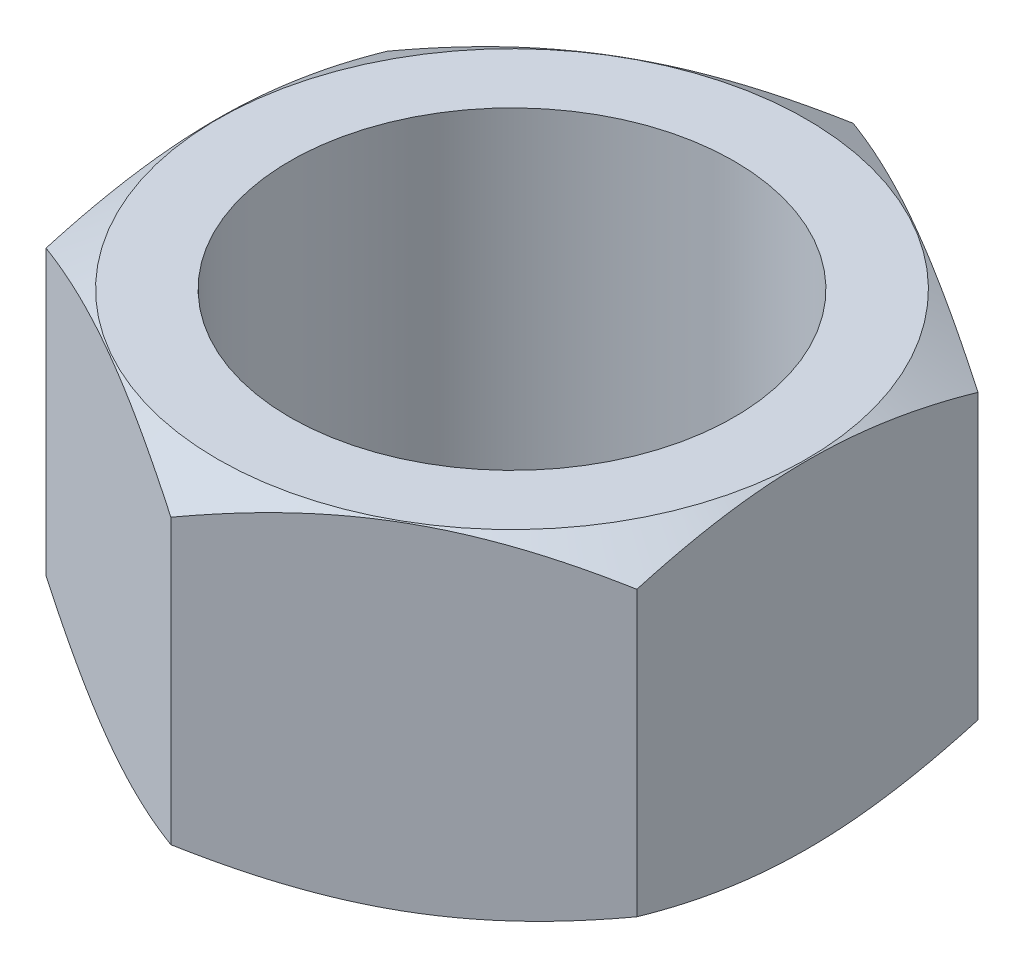
SolidWorks part; units mm, degrees
ref_plane "Front Plane" through (0, 0, 0) normal (0, 0, 1) x (1, 0, 0)
ref_plane "Top Plane" through (0, 0, 0) normal (0, 1, 0) x (1, 0, 0)
ref_plane "Right Plane" through (0, 0, 0) normal (1, 0, 0) x (0, 0, -1)
sketch "Sketch2" plane through (0, 0, 0) normal (0, 1, 0) x (1, 0, 0)
  line L1 (0, -0.2021) -> (0.175, -0.101)
  line L2 (0.175, -0.101) -> (0.175, 0.101)
  line L3 (0.175, 0.101) -> (0, 0.2021)
  line L4 (0, 0.2021) -> (-0.175, 0.101)
  line L5 (-0.175, 0.101) -> (-0.175, -0.101)
  line L6 (-0.175, -0.101) -> (0, -0.2021)
  circle A0 centre (0, 0) radius 0.175 construction
  circle A1 centre (0, 0) radius 0.1315
  dimension "D2" = 0.263
  dimension "D1" = 0.35
extrude "Boss-Extrude1" add sketch "Sketch2" along normal mid plane 0.2
sketch "Sketch3" plane through (0, 0.1, 0) normal (0, 1, 0) x (1, 0, 0)
  circle A0 centre (0, 0) radius 0.1744
extrude "Cut-Extrude1" cut sketch "Sketch3" against normal blind 0.2 draft 60 flip side to cut
sketch "Sketch4" plane through (0, -0.1, 0) normal (0, -1, 0) x (1, 0, 0)
  circle A0 centre (0, 0) radius 0.1743
extrude "Cut-Extrude2" cut sketch "Sketch4" against normal blind 0.2 draft 60 flip side to cut
